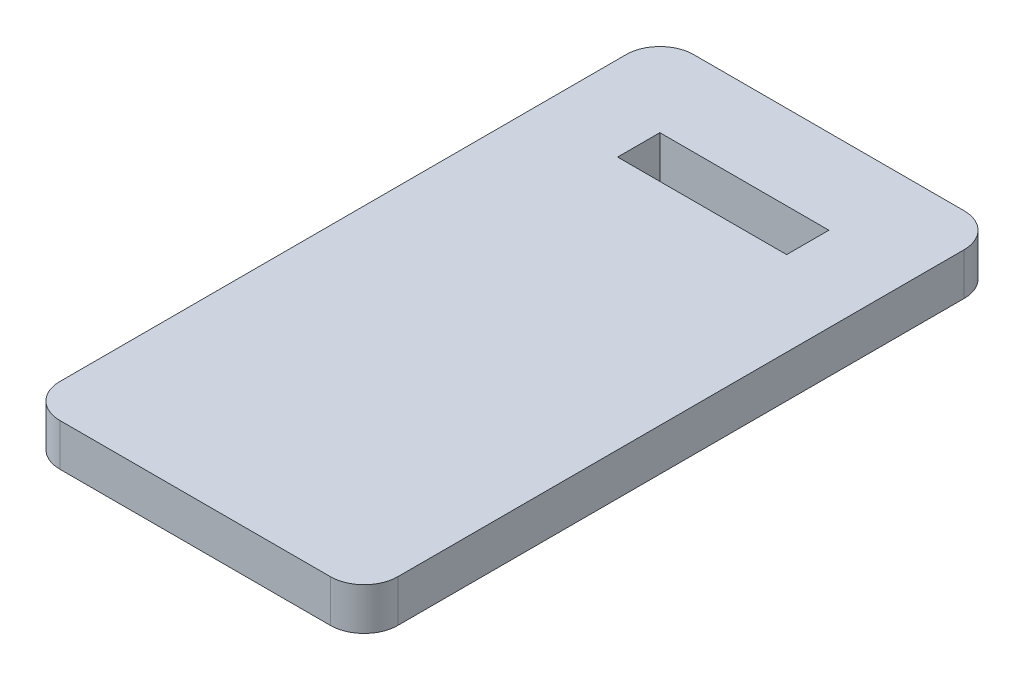
SolidWorks part; units mm, degrees
material "Acrylic (Medium-high impact)"
ref_plane "Front Plane" through (0, 0, 0) normal (0, 0, 1) x (1, 0, 0)
ref_plane "Top Plane" through (0, 0, 0) normal (0, 1, 0) x (1, 0, 0)
ref_plane "Right Plane" through (0, 0, 0) normal (1, 0, 0) x (0, 0, -1)
ref_plane "Plane1" through (0, 0, 0) normal (0, 1, 0) x (1, 0, 0)
sketch "Sketch1" plane through (0, 0, 0) normal (0, 1, 0) x (1, 0, 0)
  line L1 (0, 0) -> (25.4, 0)
  line L2 (0, 0) -> (0, 47.625)
  line L3 (0, 47.625) -> (25.4, 47.625)
  line L4 (25.4, 0) -> (25.4, 47.625)
  dimension "D1" = 47.625
  dimension "D2" = 25.4
extrude "Boss-Extrude1" add sketch "Sketch1" along normal blind 3.175
ref_plane "Plane2" through (0, 3.175, 0) normal (0, 1, 0) x (1, 0, 0)
sketch "Sketch2" plane through (0, 3.175, 0) normal (0, 1, 0) x (1, 0, 0)
  line L1 (6.35, 41.275) -> (19.05, 41.275)
  line L2 (6.35, 41.275) -> (6.35, 38.1)
  line L3 (6.35, 38.1) -> (19.05, 38.1)
  line L4 (19.05, 41.275) -> (19.05, 38.1)
  line L5 (0, 47.625) -> (0, 0) construction
  line L6 (25.4, 47.625) -> (0, 47.625) construction
  dimension "D1" = 12.7
  dimension "D2" = 3.175
  dimension "D3" = 6.35
  dimension "D4" = 6.35
extrude "Cut-Extrude1" cut sketch "Sketch2" against normal through all
fillet "Fillet1" radius 2.54 4 edges at (0, 1.5875, -47.625) (25.4, 1.5875, -47.625) (25.4, 1.5875, 0) (0, 1.5875, 0)
